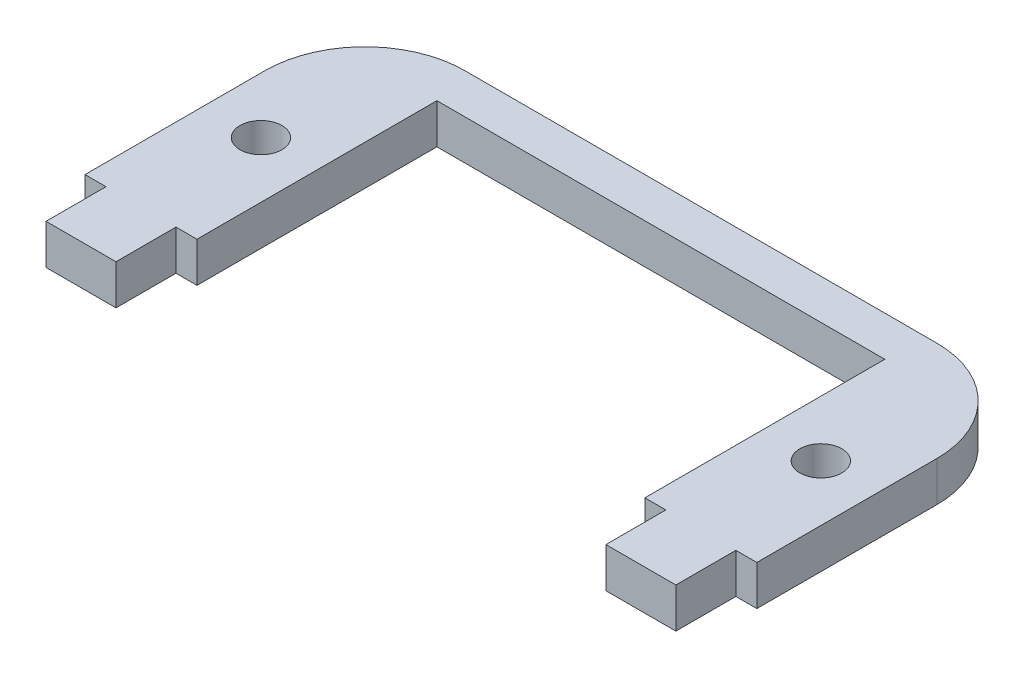
SolidWorks part; units mm, degrees
ref_plane "Front" through (0, 0, 0) normal (0, 0, 1) x (1, 0, 0)
ref_plane "Top" through (0, 0, 0) normal (0, 1, 0) x (1, 0, 0)
ref_plane "Right" through (0, 0, 0) normal (1, 0, 0) x (0, 0, -1)
sketch "Croquis1" plane through (0, 0, 0) normal (0, 1, 0) x (1, 0, 0)
  line L0 (-319.2972, 0) -> (15645.5623, 0) construction
  line L1 (0, -319.2972) -> (0, 15645.5623) construction
  line L2 (-11.2, 0) -> (-11.2, 12)
  line L3 (-11.2, 12) -> (11.2, 12)
  line L4 (11.2, 12) -> (11.2, 0)
  line L5 (-16.8, 0) -> (-16.8, 9)
  line L6 (-11.8, 14) -> (11.8, 14)
  line L7 (16.8, 9) -> (16.8, 0)
  line L8 (-1011.2, 6) -> (48988.8, 6) construction
  line L9 (-16.8, 0) -> (-15.75, 0)
  line L10 (-15.75, 0) -> (-15.75, -3)
  line L11 (-15.75, -3) -> (-12.25, -3)
  line L12 (-12.25, -3) -> (-12.25, 0)
  line L13 (-12.25, 0) -> (-11.2, 0)
  line L14 (-11.2, 0) -> (-11.2883, -0.0205)
  line L15 (12.25, 0) -> (11.2, 0)
  line L16 (12.25, -3) -> (12.25, 0)
  line L17 (15.75, -3) -> (12.25, -3)
  line L18 (15.75, 0) -> (15.75, -3)
  line L19 (16.8, 0) -> (15.75, 0)
  line L20 (-16.8, 17.6) -> (16.8, 17.6) construction
  line L21 (-16.8, 0) -> (-16.8, 17.6) construction
  line L22 (16.8, 17.6) -> (16.8, 0) construction
  line L23 (6, -319.2972) -> (6, 15645.5623) construction
  line L24 (-6, -319.2972) -> (-6, 15645.5623) construction
  circle A0 centre (-14, 6) radius 1.05
  circle A1 centre (14, 6) radius 1.05
  arc A2 (-16.8, 9) -> (-11.8, 14) centre (-11.8, 9) cw
  arc A3 (16.8, 9) -> (11.8, 14) centre (11.8, 9) ccw
  circle A4 centre (0, 14.8) radius 1.05 construction
  circle A5 centre (-12, 14.8) radius 1.05 construction
  circle A6 centre (12, 14.8) radius 1.05 construction
  point P16 (-11.2, 6)
  point P46 (16.8, 14)
  dimension "D5" = 2.1
  dimension "D6" = 2.8
  dimension "D9" = 5
  dimension "D10" = 14
  dimension "D11" = 2.1
  dimension "D12" = 2.8
  dimension "D4" = 5
  dimension "D1" = 12
  dimension "D2" = 22.4
  dimension "D3" = 3
  dimension "D7" = 3.5
  dimension "D8" = 1.05
extrude "Saliente-Extruir1" add sketch "Croquis1" along normal blind 2
